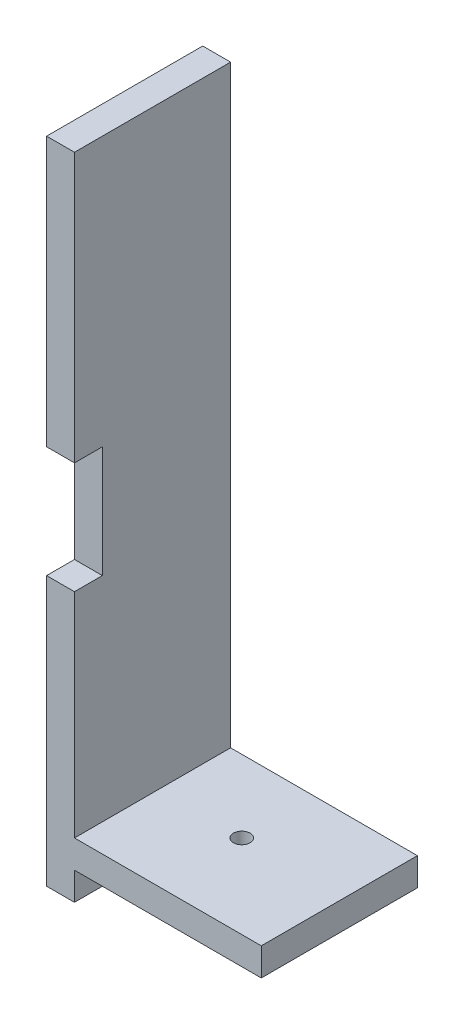
SolidWorks part; units mm, degrees
ref_plane "前基準面" through (0, 0, 0) normal (0, 0, 1) x (1, 0, 0)
ref_plane "上基準面" through (0, 0, 0) normal (0, 1, 0) x (1, 0, 0)
ref_plane "右基準面" through (0, 0, 0) normal (1, 0, 0) x (0, 0, -1)
sketch "草圖1" plane through (0, 0, 0) normal (0, 0, 1) x (1, 0, 0)
  line L0 (-17.4514, -6.1961) -> (-17.4514, -11.1961)
  line L1 (-22.4514, 105.3039) -> (-17.4514, 105.3039)
  line L2 (-22.4514, 105.3039) -> (-22.4514, -11.1961)
  line L3 (-22.4514, -11.1961) -> (-17.4514, -11.1961)
  line L4 (-17.4514, 105.3039) -> (-17.4514, 100.3039)
  line L5 (-17.4514, -6.1961) -> (16.0486, -6.1961)
  line L6 (-17.4514, 95.3039) -> (-17.4514, -1.1961)
  line L7 (-17.4514, -1.1961) -> (16.0486, -1.1961)
  line L8 (16.0486, -6.1961) -> (16.0486, -1.1961)
  line L10 (-17.4514, 100.3039) -> (-17.4514, 95.3039)
  dimension "D1" = 5
  dimension "D2" = 5
  dimension "D3" = 33.5
  dimension "D4" = 116.5
  dimension "D5" = 5
extrude "填料-伸長1" add sketch "草圖1" along normal blind 28
sketch "草圖2" plane through (0, 0, 28) normal (0, 0, -1) x (-1, 0, 0)
  line L0 (17.4514, -1.1961) -> (17.4514, 105.3039) construction
  line L1 (17.4514, 37.0539) -> (22.4514, 37.0539)
  line L2 (17.4514, 37.0539) -> (17.4514, 57.0539)
  line L3 (17.4514, 57.0539) -> (22.4514, 57.0539)
  line L4 (22.4514, 37.0539) -> (22.4514, 57.0539)
  line L5 (22.4514, 105.3039) -> (22.4514, -11.1961) construction
  line L6 (17.4514, 105.3039) -> (22.4514, 105.3039) construction
  dimension "D1" = 20
  dimension "D2" = 48.25
extrude "除料-伸長1" cut sketch "草圖2" along normal blind 5
sketch "草圖3" plane through (0, -6.1961, 0) normal (0, -1, 0) x (1, 0, 0)
  line L2 (-17.4514, 28) -> (-17.4514, 0) construction
  line L3 (-17.4514, 28) -> (16.0486, 28) construction
  circle A0 centre (-2.4514, 13) radius 1.5
  point P6 (-17.4514, 15.4745)
  dimension "D1" = 3
  dimension "D2" = 15
  dimension "D3" = 15
extrude "除料-伸長2" cut sketch "草圖3" against normal through all contours A0
